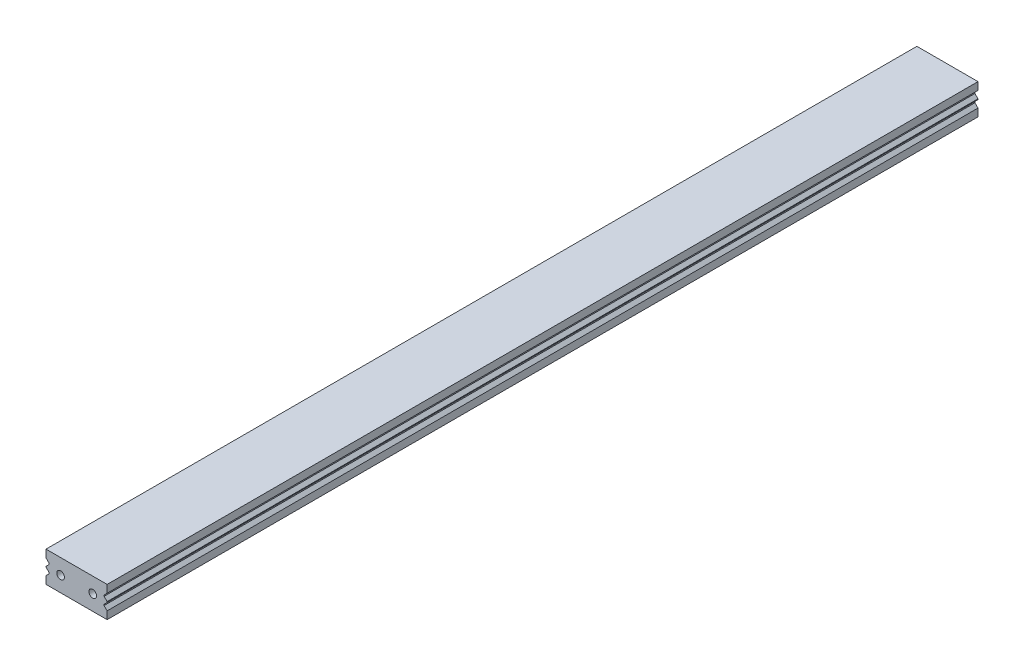
SolidWorks part; units mm, degrees
material "1.4511 (X3CrNb17)"
ref_plane "前视基准面" through (0, 0, 0) normal (0, 0, 1) x (1, 0, 0)
ref_plane "上视基准面" through (0, 0, 0) normal (0, 1, 0) x (1, 0, 0)
ref_plane "右视基准面" through (0, 0, 0) normal (1, 0, 0) x (0, 0, -1)
sketch "草图1" plane through (0, 0, 0) normal (0, 0, 1) x (1, 0, 0)
  line L0 (10, 0.25) -> (10, -0.25)
  line L1 (10, 5) -> (10, 10)
  line L2 (12, 3) -> (12, 2.25)
  line L3 (10, 10) -> (30, 10)
  line L4 (30, 10) -> (30, -10)
  line L5 (30, -10) -> (10, -10)
  line L6 (12, -2.25) -> (12, -3)
  line L7 (10, -10) -> (10, -5)
  line L8 (10, 5) -> (12, 3)
  line L9 (12, 2.25) -> (10, 0.25)
  line L10 (10, -0.25) -> (12, -2.25)
  line L11 (12, -3) -> (10, -5)
  point P0 (12, 0.25)
  point P4 (0, 0)
  point P6 (12, 5)
  point P11 (12, -0.25)
  point P12 (12, -5)
  dimension "D2" = 5
  dimension "D3" = 4.75
  dimension "D4" = 5
  dimension "D5" = 20
extrude "凸台-拉伸1" add sketch "草图1" against normal blind 570
ref_plane "基准面1" through (30, 0, 0) normal (1, 0, 0) x (0, 0, -1)
mirror "镜向1" about plane through (30, 0, 0) normal (1, 0, 0) of "凸台-拉伸1"
sketch "草图2" plane through (0, 0, -570) normal (0, 0, -1) x (-1, 0, 0)
  line L0 (-40, 0) -> (-20, 0) construction
  point P4 (-30, 0)
  dimension "D1" = 20
hole_wizard "M6 螺纹孔1" positions "草图3" profile "草图4" tap size "M6" standard "GB"
sketch "草图3" plane through (0, 0, -570) normal (0, 0, -1) x (-1, 0, 0)
  point P0 (-40, 0)
  point P3 (-20, 0)
sketch "草图4" plane through (40, 0, -570) normal (1, 0, 0) x (0, 1, 0)
  line L0 (0, 0) -> (0, 18.5022)
  line L1 (0, 18.5022) -> (2.5, 17)
  line L2 (2.5, 17) -> (2.5, 0)
  line L5 (2.5, 0) -> (0, 0)
  line L10 (0, 18.5022) -> (-2.5, 17) construction
  line L11 (0, -6.35) -> (0, 107.95) construction
  dimension "螺纹孔钻头直径" = 5
  dimension "螺纹孔钻头深度" = 17
  dimension "导头角度" = 118
cosmetic thread "孔螺蚊线1" parameters "D1"=12, "D2"=6
cosmetic thread "孔螺蚊线2" parameters "D1"=12, "D2"=6
sketch "草图5" plane through (0, 0, 0) normal (0, 0, 1) x (1, 0, 0)
  line L0 (19.5727, 0) -> (40.5727, 0) construction
  line L1 (10, -10) -> (50, -10) construction
  point P4 (30.0727, 0)
hole_wizard "M6 螺纹孔2" positions "草图6" profile "草图8" tap size "M6" standard "GB"
sketch "草图6" plane through (0, 0, 0) normal (0, 0, 1) x (1, 0, 0)
  point P0 (19.5727, 0)
  point P3 (40.5727, 0)
sketch "草图8" plane through (19.5727, 0, 0) normal (1, 0, 0) x (0, -1, 0)
  line L0 (0, 0) -> (0, 18.5022)
  line L1 (0, 18.5022) -> (2.5, 17)
  line L2 (2.5, 17) -> (2.5, 0)
  line L5 (2.5, 0) -> (0, 0)
  line L10 (0, 18.5022) -> (-2.5, 17) construction
  line L11 (0, -6.35) -> (0, 107.95) construction
  dimension "螺纹孔钻头直径" = 5
  dimension "螺纹孔钻头深度" = 17
  dimension "导头角度" = 118
cosmetic thread "孔螺蚊线3" parameters "D1"=12, "D2"=6
cosmetic thread "孔螺蚊线4" parameters "D1"=12, "D2"=6
